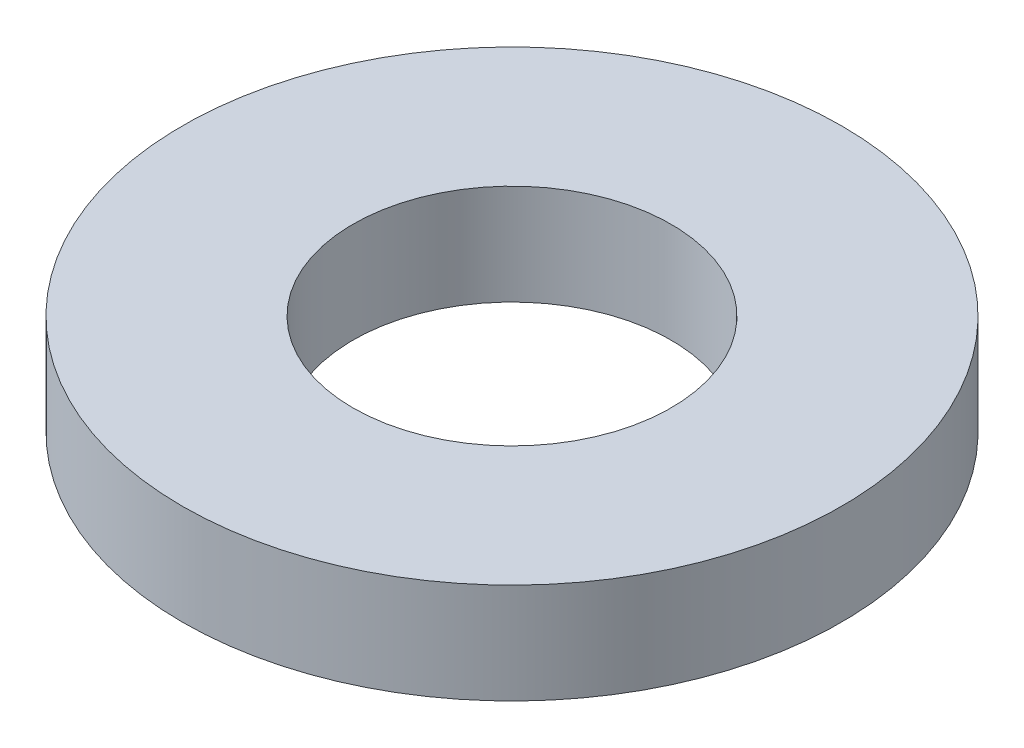
SolidWorks part; units mm, degrees
ref_plane "Plan de face" through (0, 0, 0) normal (0, 0, 1) x (1, 0, 0)
ref_plane "Plan de dessus" through (0, 0, 0) normal (0, 1, 0) x (1, 0, 0)
ref_plane "Plan de droite" through (0, 0, 0) normal (1, 0, 0) x (0, 0, -1)
ref_plane "Plan1" through (0, 0, 10.4) normal (0, 0, -1) x (-1, 0, 0)
sketch "Esquisse1" plane through (0, 0, 10.4) normal (0, 0, -1) x (-1, 0, 0)
  line L0 (-45.5578, -18.9871) -> (-45.5578, -21.6371)
  line L1 (-45.5578, -21.6371) -> (-41.0578, -21.6371)
  line L2 (-41.0578, -21.6371) -> (-41.0578, -18.9871)
  line L3 (-41.0578, -18.9871) -> (-45.5578, -18.9871)
  line L4 (-36.8578, -21.6371) -> (-36.8578, -19.1371) construction
  dimension "D1" = 2.65
  dimension "D2" = 17.4
  dimension "D3" = 8.4
revolve "Révolution1" add sketch "Esquisse1" angle 360 about L4
